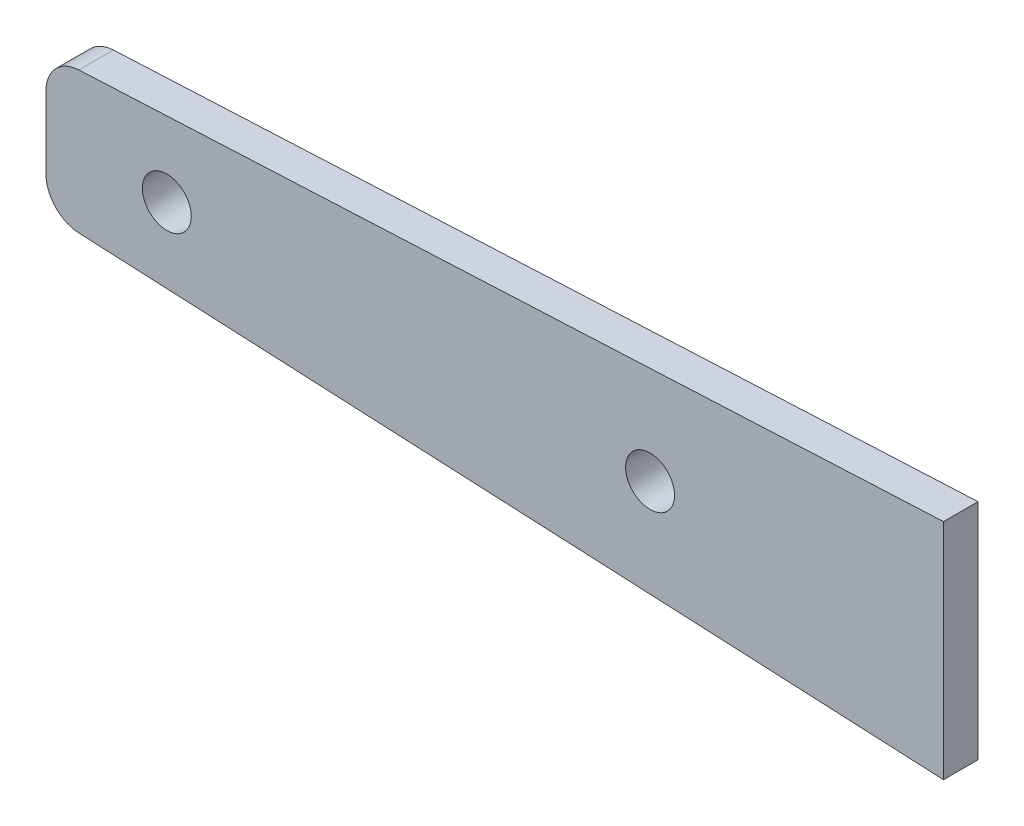
SolidWorks part; units mm, degrees
material "ASTM A36 Steel"
ref_plane "X-Y Datum" through (0, 0, 0) normal (0, 0, 1) x (1, 0, 0)
ref_plane "X-Z Datum" through (0, 0, 0) normal (0, 1, 0) x (1, 0, 0)
ref_plane "Y-Z Datum" through (0, 0, 0) normal (1, 0, 0) x (0, 0, -1)
sketch "Sketch1" plane through (0, 0, 0) normal (0, 0, 1) x (1, 0, 0)
  line L0 (-22.225, 0) -> (22.225, 0) construction
  line L1 (33.3375, 9.525) -> (33.3375, -9.525) construction
  line L6 (-33.3375, 9.525) -> (33.3375, 9.525) construction
  line L7 (-33.3375, 9.525) -> (-33.3375, -9.525) construction
  line L12 (-33.3375, -9.525) -> (33.3375, -9.525) construction
  line L13 (33.3375, 9.525) -> (33.3375, -9.525) construction
  line L14 (-33.3375, 9.525) -> (33.3375, -9.525) construction
  line L15 (-33.3375, -9.525) -> (33.3375, 9.525) construction
  line L16 (-33.3375, 6.35) -> (-33.3375, -6.35)
  line L17 (-33.3375, 6.35) -> (33.3375, 9.525)
  line L18 (-33.3375, -6.35) -> (33.3375, -9.525)
  line L19 (49.2125, 10.281) -> (49.2125, -10.281)
  line L21 (33.3375, 9.525) -> (33.3375, -9.525) construction
  line L24 (33.3375, 9.525) -> (49.2125, 10.281)
  line L25 (33.3375, -9.525) -> (49.2125, -10.281)
  circle A2 centre (-22.225, 0) radius 2 construction
  circle A3 centre (22.225, 0) radius 2 construction
  point P6 (0, 0)
  point P8 (0, 0)
  point P14 (33.3375, 0)
  point P16 (-33.3375, 0)
  point P19 (49.2125, 0)
  dimension "D1" = 4
  dimension "D2" = 19.05
  dimension "D3" = 66.675
  dimension "D4" = 44.45
  dimension "D5" = 12.7
  dimension "D6" = 15.875
extrude "Boss-Extrude1" add sketch "Sketch1" along normal blind 3.175
hole_wizard "M4 Clearance Hole2" positions "Sketch9" profile "Sketch8" hole size "M4" standard "ANSI Metric" end condition through all
sketch "Sketch9" plane through (0, 0, 3.175) normal (0, 0, 1) x (1, 0, 0)
  point P0 (-22.225, 0)
  point P3 (22.225, 0)
sketch "Sketch8" plane through (-22.225, 0, 3.175) normal (1, 0, 0) x (0, -1, 0)
  line L0 (0, 0) -> (0, 3.175)
  line L1 (0, 3.175) -> (2.25, 3.175)
  line L2 (2.25, 3.175) -> (2.25, 0)
  line L5 (2.25, 0) -> (0, 0)
  line L11 (0, -6.35) -> (0, 107.95) construction
  dimension "Thru Hole Dia." = 4.5
  dimension "Thru Hole Depth" = 3.175
fillet "Fillet1" radius 3.175 2 edges at (-33.3375, -6.35, 1.5875) (-33.3375, 6.35, 1.5875)
